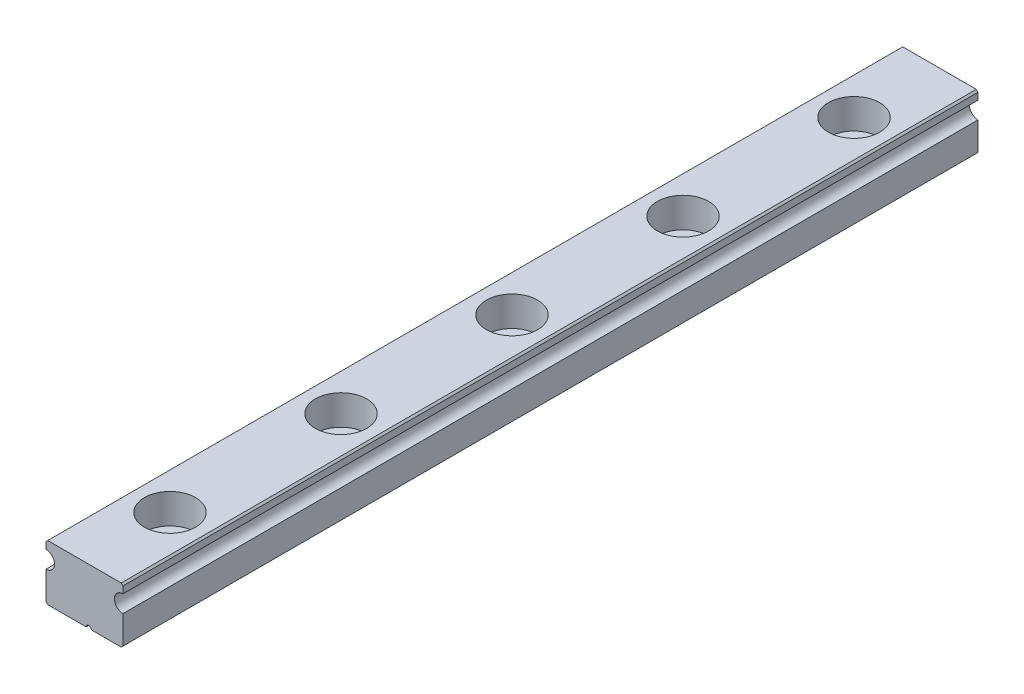
SolidWorks part; units mm, degrees
material "镀铬不锈钢"
ref_plane "前视基准面" through (0, 0, 0) normal (0, 0, 1) x (1, 0, 0)
ref_plane "上视基准面" through (0, 0, 0) normal (0, 1, 0) x (1, 0, 0)
ref_plane "右视基准面" through (0, 0, 0) normal (1, 0, 0) x (0, 0, -1)
sketch "草图1" plane through (0, 0, 0) normal (0, 0, 1) x (1, 0, 0)
  line L2 (4.5, 5.5) -> (4.5, 6.3)
  line L3 (-4.3, 6.5) -> (-4.5, 6.3)
  line L4 (4.5, 0.2) -> (4.5, 3.5)
  line L5 (4.3, 6.5) -> (-4.3, 6.5)
  line L6 (4.5, 6.3) -> (4.3, 6.5)
  line L7 (-4.3, 0) -> (0.2, 0)
  line L8 (4.3, 0) -> (4.5, 0.2)
  line L9 (0.8, 0) -> (4.3, 0)
  line L10 (-4.5, 0.2) -> (-4.3, 0)
  line L11 (0, 6.5) -> (0, 0) construction
  line L12 (-4.5, 3.5) -> (-4.5, 0.2)
  line L13 (-4.5, 6.3) -> (-4.5, 5.5)
  arc A0 (-4.5, 3.5) -> (-4.5, 5.5) centre (-4.5, 4.5) ccw
  arc A1 (0.8, 0) -> (0.2, 0) centre (0.5, 0) ccw
  arc A2 (4.5, 5.5) -> (4.5, 3.5) centre (4.5, 4.5) ccw
extrude "凸台-拉伸1" add sketch "草图1" against normal blind 220
hole_wizard "M3 六角凹头螺钉的柱形沉头孔1" positions "草图3" profile "草图2" counterbore size "M3" standard "ISO" end condition through all
sketch "草图3" plane through (0.7549, 6.5, 19.3435) normal (0, 1, 0) x (-1, 0, 0)
  point P0 (0.7549, -29.3435)
  dimension "D1" = 10
sketch "草图2" plane through (0, 6.5, -10) normal (1, 0, 0) x (0, 0, 1)
  line L0 (0, 0) -> (0, 6.5)
  line L1 (0, 6.5) -> (1.75, 6.5)
  line L3 (1.75, 6.5) -> (1.75, 3.5)
  line L4 (1.75, 3.5) -> (3, 3.5)
  line L5 (3, 3.5) -> (3, 0)
  line L7 (3, 0) -> (0, 0)
  line L11 (0, -6.35) -> (0, 107.95) construction
  dimension "通孔孔直径" = 3.5
  dimension "通孔孔深度" = 6.5
  dimension "柱形沉头孔直径" = 6
  dimension "柱形沉头孔深度" = 3.5
pattern_linear "阵列(线性)1" count 11 spacing 20 along (0, 0, -1) of "M3 六角凹头螺钉的柱形沉头孔1"
sketch "草图6" plane through (0, 6.5, 0) normal (0, 1, 0) x (1, 0, 0)
  line L0 (0, 10) -> (0, 30) construction
  text T0 "HIWIN MGN9" font "Century Gothic" height 1.5
extrude "切除-拉伸1" cut sketch "草图6" against normal blind 0.1
sketch "草图8" plane through (0, 6.5, 0) normal (0, 1, 0) x (1, 0, 0)
  line L0 (0, 110) -> (57.3697, 110) construction
  line L18 (25, 180) -> (-25, 180)
  line L19 (25, 180) -> (25, 240)
  line L20 (25, 240) -> (-25, 240)
  line L21 (-25, 180) -> (-25, 240)
  line L22 (25, 180) -> (-25, 240) construction
  line L23 (25, 240) -> (-25, 180) construction
  line L24 (25, -60) -> (-25, -60)
  line L29 (25, -60) -> (25, 80)
  line L30 (25, 80) -> (-25, 80)
  line L31 (-25, -60) -> (-25, 80)
  line L32 (25, -60) -> (-25, 80) construction
  line L33 (25, 80) -> (-25, -60) construction
  point P2 (0, 210)
  point P9 (0, 10)
  point P14 (0, 10)
  dimension "D1" = 50
  dimension "D2" = 60
  dimension "D3" = 50
  dimension "D4" = 140
extrude "切除-拉伸2" cut sketch "草图8" against normal through all
